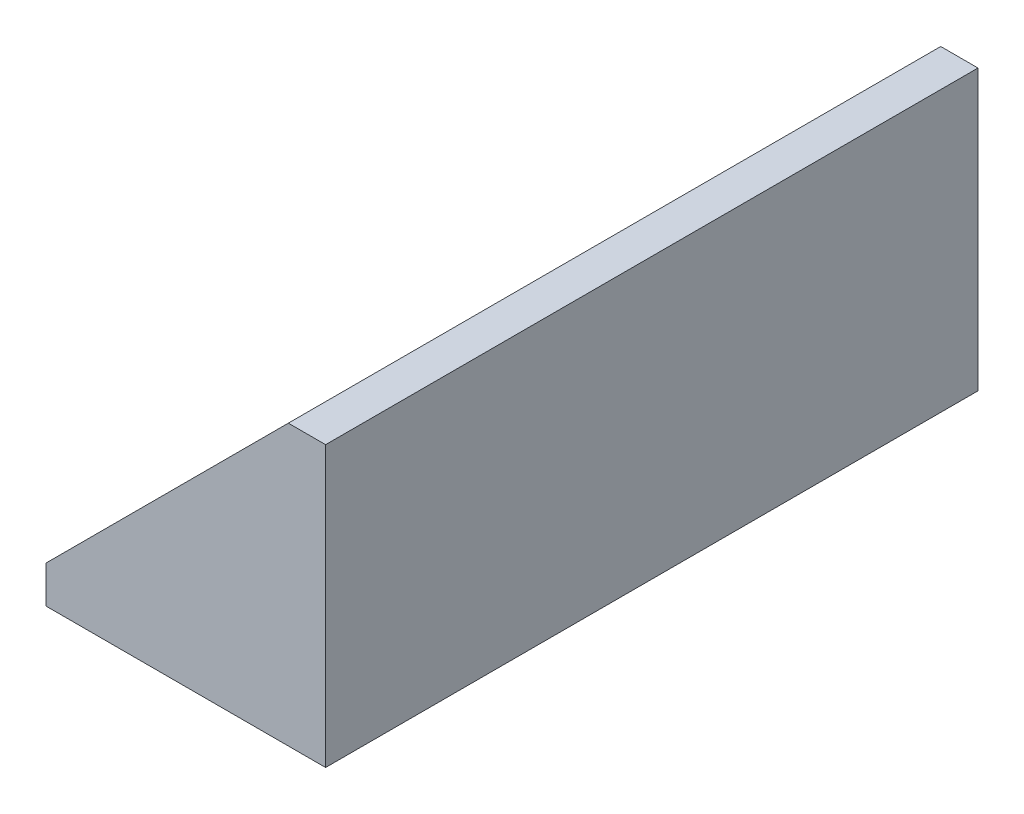
SolidWorks part; units mm, degrees
ref_plane "Front Plane" through (0, 0, 0) normal (0, 0, 1) x (1, 0, 0)
ref_plane "Top Plane" through (0, 0, 0) normal (0, 1, 0) x (1, 0, 0)
ref_plane "Right Plane" through (0, 0, 0) normal (1, 0, 0) x (0, 0, -1)
sketch "Sketch1" plane through (0, 0, 0) normal (0, 0, 1) x (1, 0, 0)
  line L0 (0, 0) -> (30, 0)
  line L1 (30, 0) -> (30, 30)
  line L2 (30, 30) -> (26, 30)
  line L3 (0, 0) -> (0, 4)
  line L4 (0, 4) -> (26, 4)
  line L5 (26, 4) -> (26, 30)
extrude "Boss-Extrude1" add sketch "Sketch1" along normal blind 70
sketch "Sketch2" plane through (0, 0, 70) normal (0, 0, 1) x (1, 0, 0)
  line L0 (26, 30) -> (0, 4)
  line L1 (0, 4) -> (26, 4)
  line L2 (26, 4) -> (26, 30)
extrude "Boss-Extrude2" add sketch "Sketch2" against normal blind 4
sketch "Sketch3" plane through (0, 0, 0) normal (0, 0, -1) x (-1, 0, 0)
  line L0 (-26, 30) -> (0, 4)
  line L1 (0, 4) -> (-26, 4)
  line L2 (-26, 4) -> (-26, 30)
extrude "Boss-Extrude3" add sketch "Sketch3" against normal blind 4
ref_plane "Plane1" through (0, 0, 35) normal (0, 0, -1) x (-1, 0, 0)
sketch "Sketch4" plane through (0, 0, 35) normal (0, 0, -1) x (-1, 0, 0)
  line L3 (-26, 30) -> (-26, 4)
  line L4 (0, 4) -> (-26, 30)
  line L5 (-26, 4) -> (0, 4)
  line L6 (-26, 30) -> (-26, 4)
  line L7 (0, 4) -> (-26, 30)
  line L8 (-26, 4) -> (0, 4)
  dimension "D1" = 0
extrude "Boss-Extrude4" add sketch "Sketch4" along normal blind 2 and the other way blind 2
